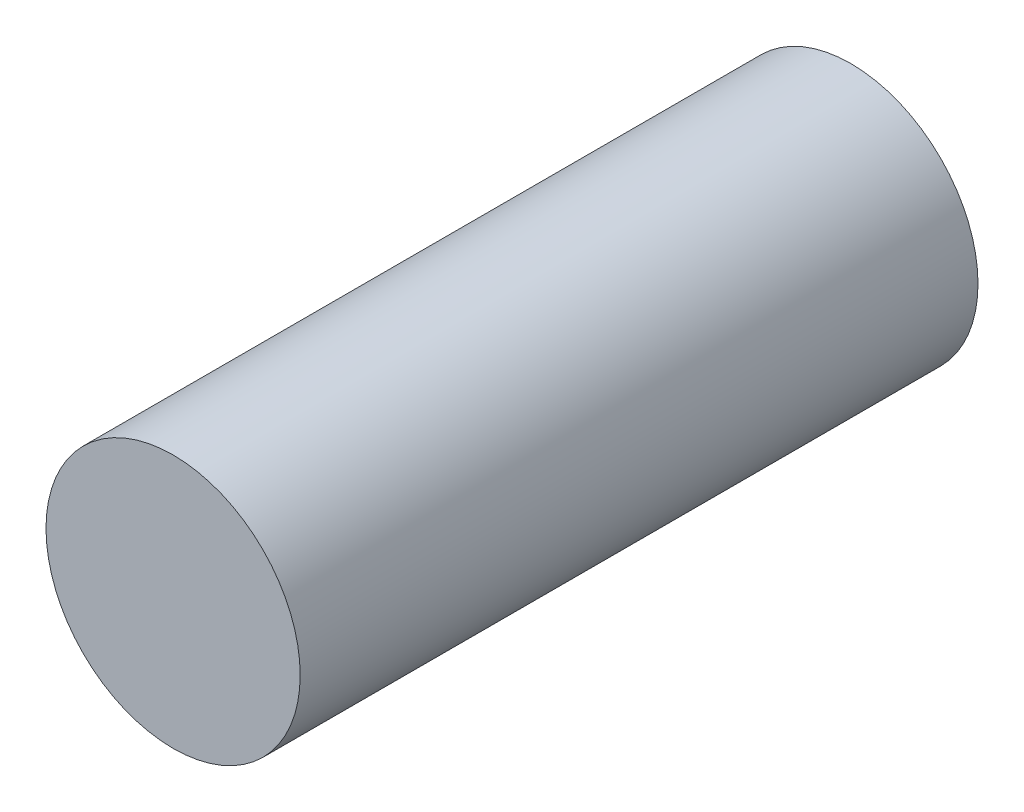
SolidWorks part; units mm, degrees
ref_plane "前视基准面" through (0, 0, 0) normal (0, 0, 1) x (1, 0, 0)
ref_plane "上视基准面" through (0, 0, 0) normal (0, 1, 0) x (1, 0, 0)
ref_plane "右视基准面" through (0, 0, 0) normal (1, 0, 0) x (0, 0, -1)
other "Configuration Table"
sketch "Sketch1" plane through (0, 0, 0) normal (0, 0, 1) x (1, 0, 0)
  circle A0 centre (0, 0) radius 7.5
  dimension "D1" = 15
extrude "Boss-Extrude1" add sketch "Sketch1" along normal blind 40
